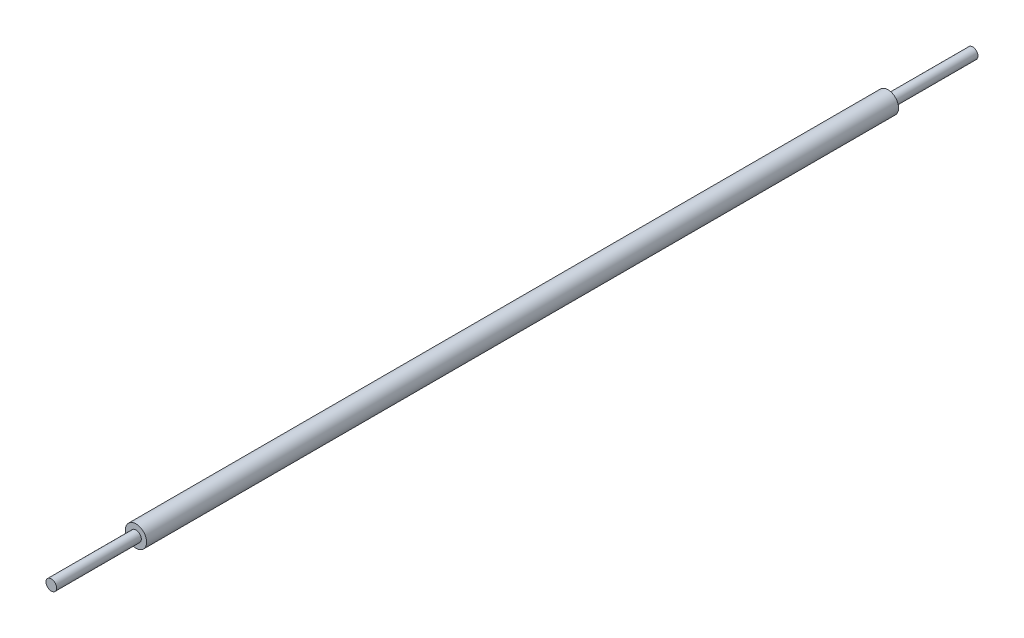
SolidWorks part; units mm, degrees
ref_plane "Front Plane" through (0, 0, 0) normal (0, 0, 1) x (1, 0, 0)
ref_plane "Top Plane" through (0, 0, 0) normal (0, 1, 0) x (1, 0, 0)
ref_plane "Right Plane" through (0, 0, 0) normal (1, 0, 0) x (0, 0, -1)
sketch "Sketch1" plane through (0, 0, 0) normal (0, 0, 1) x (1, 0, 0)
  circle A0 centre (0, 0) radius 2.5
  dimension "D1" = 5
extrude "Boss-Extrude1" add sketch "Sketch1" along normal blind 177.5
sketch "Sketch2" plane through (0, 0, 177.5) normal (0, 0, 1) x (1, 0, 0)
  circle A0 centre (0, 0) radius 1.25
  dimension "D1" = 2.5
extrude "Boss-Extrude2" add sketch "Sketch2" along normal blind 20
sketch "Sketch3" plane through (0, 0, 0) normal (0, 0, -1) x (-1, 0, 0)
  circle A0 centre (0, 0) radius 1.25
  dimension "D1" = 2.5
extrude "Boss-Extrude3" add sketch "Sketch3" along normal blind 20
